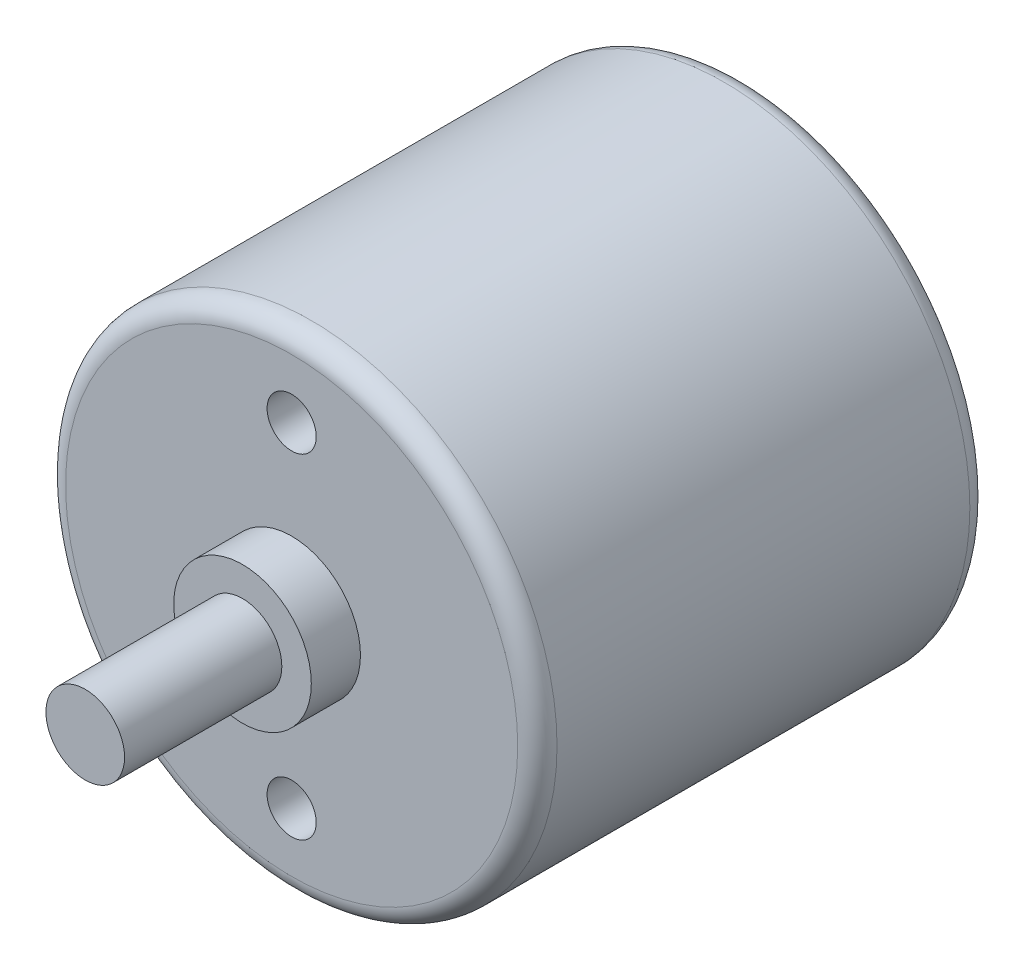
SolidWorks part; units mm, degrees
material "201.0-T43 Molde de fundição com isolamento (SS)"
ref_plane "Plano frontal" through (0, 0, 0) normal (0, 0, 1) x (1, 0, 0)
ref_plane "Plano superior" through (0, 0, 0) normal (0, 1, 0) x (1, 0, 0)
ref_plane "Plano direito" through (0, 0, 0) normal (1, 0, 0) x (0, 0, -1)
sketch "Esboço1" plane through (0, 0, 0) normal (0, 0, 1) x (1, 0, 0)
  circle A0 centre (0, 0) radius 12.5
  dimension "D1" = 25
extrude "Ressalto-extrusão1" add sketch "Esboço1" along normal blind 23
sketch "Esboço2" plane through (0, 0, 23) normal (0, 0, 1) x (1, 0, 0)
  circle A0 centre (0, 0) radius 3.5
  dimension "D1" = 7
extrude "Ressalto-extrusão2" add sketch "Esboço2" along normal blind 2.5
sketch "Esboço3" plane through (0, 0, 25.5) normal (0, 0, 1) x (1, 0, 0)
  circle A0 centre (0, 0) radius 2
  dimension "D1" = 4
fillet "Filete1" radius 1 2 edges at (12.5, 0, 23) (12.5, 0, 0)
extrude "Ressalto-extrusão3" add sketch "Esboço3" along normal blind 8
sketch "Esboço4" plane through (0, 0, 23) normal (0, 0, 1) x (1, 0, 0)
  circle A0 centre (0, 8.5) radius 1.25
  circle A1 centre (0, -8.5) radius 1.25
  point P8 (0, 0)
  dimension "D1" = 2.5
  dimension "D2" = 2
  dimension "D3" = 17
extrude "Corte-extrusão1" cut sketch "Esboço4" against normal blind 10
